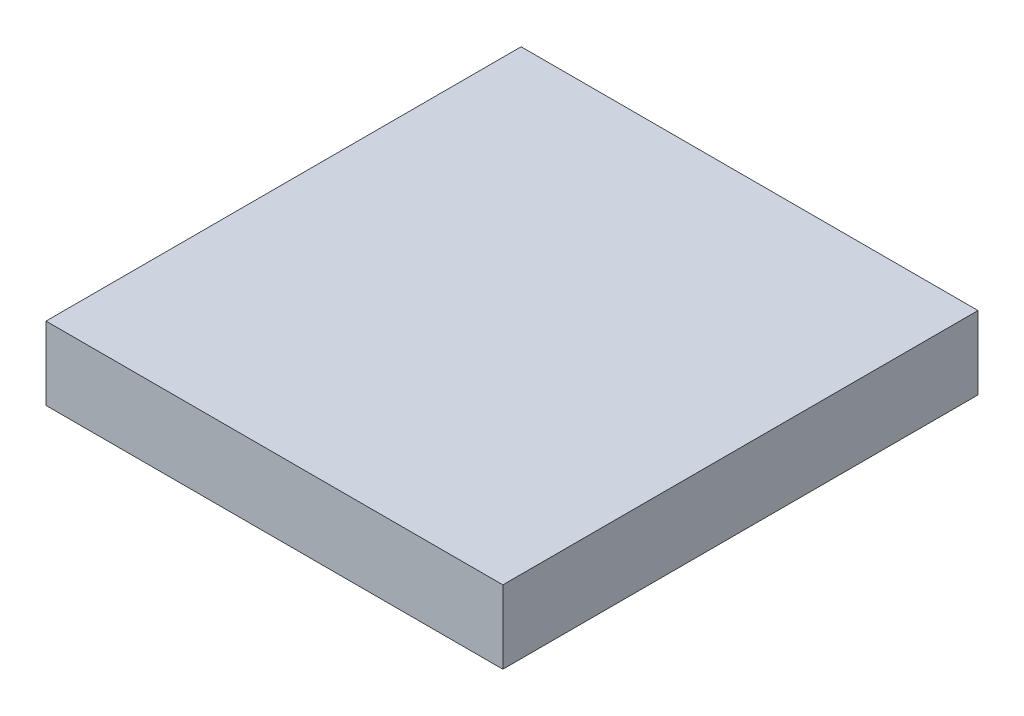
SolidWorks part; units mm, degrees
material "1.0553 (S355J0)"
ref_plane "Front Plane" through (0, 0, 0) normal (0, 0, 1) x (1, 0, 0)
ref_plane "Top Plane" through (0, 0, 0) normal (0, 1, 0) x (1, 0, 0)
ref_plane "Right Plane" through (0, 0, 0) normal (1, 0, 0) x (0, 0, -1)
sketch "Sketch1" plane through (0, 0, 0) normal (0, 1, 0) x (1, 0, 0)
  line L0 (0, -236.5196) -> (0, 124.6072) construction
  line L1 (-250, 0) -> (250, 0)
  line L2 (-250, 0) -> (-250, 520)
  line L3 (-250, 520) -> (250, 520)
  line L4 (250, 0) -> (250, 520)
  dimension "D1" = 500
  dimension "D2" = 520
extrude "Boss-Extrude1" add sketch "Sketch1" against normal blind 80
